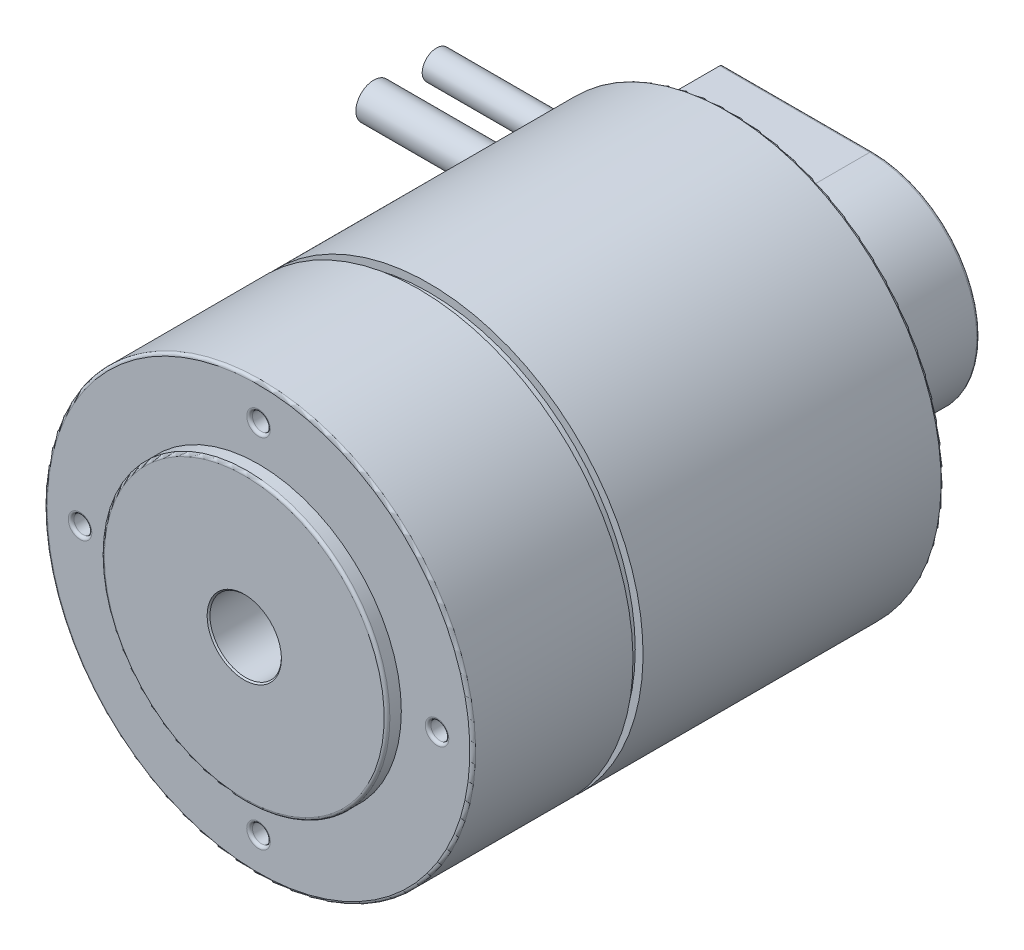
SolidWorks part; units mm, degrees
material "Copper"
ref_plane "Front Plane" through (0, 0, 0) normal (0, 0, 1) x (1, 0, 0)
ref_plane "Top Plane" through (0, 0, 0) normal (0, 1, 0) x (1, 0, 0)
ref_plane "Right Plane" through (0, 0, 0) normal (1, 0, 0) x (0, 0, -1)
sketch "Sketch1" plane through (0, 0, 0) normal (0, 0, 1) x (1, 0, 0)
  circle A0 centre (0, 0) radius 6.3437
  dimension "D1" = 12.6873
extrude "Drive Shaft Boss-Extrude1" add sketch "Sketch1" against normal blind 31.75
sketch "Sketch2" plane through (0, 0, 0) normal (0, 0, 1) x (1, 0, 0)
  line L0 (0, 0) -> (0, 8.8266) construction
  line L2 (-6.35, 10.16) -> (6.35, 10.16)
  line L3 (-6.35, 10.16) -> (-6.35, 5.08)
  line L4 (-6.35, 5.08) -> (6.35, 5.08)
  line L5 (6.35, 10.16) -> (6.35, 5.08)
  line L6 (-6.35, 10.16) -> (6.35, 5.08) construction
  line L7 (-6.35, 5.08) -> (6.35, 10.16) construction
  point P3 (0, 7.62)
  dimension "D1" = 5.08
  dimension "D2" = 12.7
  dimension "D3" = 5.08
extrude "Shaft Flat Cut-Extrude1" cut sketch "Sketch2" against normal blind 19.05
chamfer "Shaft_Chamfer1" distance 0.8128 angle 45 1 edges at (0, -6.3437, 0)
sketch "Sketch3" plane through (0, 0, -31.75) normal (0, 0, -1) x (-1, 0, 0)
  circle A0 centre (0, 0) radius 25.4
  dimension "D1" = 50.8
extrude "ServoFlangeBoss-Extrude2" add sketch "Sketch3" along normal blind 2.54
sketch "Sketch4" plane through (0, 0, -34.29) normal (0, 0, -1) x (-1, 0, 0)
  circle A0 centre (0, 0) radius 38.1
  dimension "D1" = 76.2
extrude "Motor Body Boss-Extrude3" add sketch "Sketch4" along normal blind 83.82
sketch "Sketch5" plane through (0, 0, -118.11) normal (0, 0, -1) x (-1, 0, 0)
  line L0 (0, 19.05) -> (26.67, 19.05)
  line L1 (0, -19.05) -> (26.67, -19.05)
  line L2 (26.67, 19.05) -> (26.67, -19.05)
  arc A0 (0, 19.05) -> (0, -19.05) centre (0, 0) ccw
  dimension "D1" = 38.1
  dimension "D2" = 26.67
extrude "Encoder Boss-Extrude4" add sketch "Sketch5" along normal blind 25.4
sketch "Sketch6" plane through (0, 0, 0) normal (1, 0, 0) x (0, 0, -1)
  line L0 (143.51, 0) -> (118.11, 0) construction
  line L1 (143.51, -19.05) -> (143.51, 19.05) construction
  line L2 (118.11, -19.05) -> (118.11, 19.05) construction
  circle A0 centre (125.8985, 0) radius 3.175
  circle A1 centre (137.0642, 0) radius 2.54
  dimension "D1" = 6.35
  dimension "D2" = 5.08
extrude "Cables Boss-Extrude5" add sketch "Sketch6" against normal blind 71.12
fillet "Housing Fillet1" radius 0.508 7 edges at (-13.335, -19.05, -143.51) (19.05, 0, -143.51) (-26.67, 0, -143.51) (-13.335, 19.05, -143.51) (-38.1, 0, -118.11) (-38.1, 0, -34.29) (-25.4, 0, -31.75)
sketch "Sketch7" plane through (0, 0, -34.29) normal (0, 0, 1) x (1, 0, 0)
  line L0 (0, 0) -> (50.4613, 0) construction
  line L1 (0, 0) -> (0, -50.4613) construction
  line L2 (0, 0) -> (-50.4613, 0) construction
  line L3 (0, 0) -> (0, 50.4613) construction
  circle A0 centre (0, 0) radius 31.75 construction
  circle A1 centre (31.75, 0) radius 1.5875
  circle A2 centre (0, -31.75) radius 1.5875
  circle A3 centre (-31.75, 0) radius 1.5875
  circle A4 centre (0, 31.75) radius 1.5875
  dimension "D1" = 63.5
  dimension "D2" = 3.175
  dimension "D3" = 4
extrude "Bolt Holes Cut-Extrude2" cut sketch "Sketch7" against normal blind 7.62
fillet "Bolt Hole Fillet2" radius 0.508 4 edges at (-30.1625, 0, -34.29) (1.5875, 31.75, -34.29) (33.3375, 0, -34.29) (1.5875, -31.75, -34.29)
sketch "Sketch8" plane through (0, 0, -31.75) normal (0, 0, 1) x (1, 0, 0)
  circle A0 centre (0, 0) radius 6.35
  dimension "D1" = 12.7
extrude "Shaft HoleCut-Extrude1" cut sketch "Sketch8" along normal through all and the other way blind 25.4
chamfer "Chamfer1" distance 0.254 angle 45 1 edges at (-6.35, 0, -31.75)
sketch "Sketch9" plane through (0, 0, 0) normal (1, 0, 0) x (0, 0, -1)
  line L0 (32.258, 0) -> (117.602, 0) construction
  line L1 (32.258, 25.4) -> (32.258, -25.4) construction
  line L2 (117.602, -38.1) -> (117.602, 38.1) construction
  line L4 (62.7971, 40.5325) -> (64.5879, 40.5325)
  line L5 (62.7971, 40.5325) -> (62.7971, 36.7121)
  line L6 (62.7971, 36.7121) -> (64.5879, 36.7121)
  line L7 (64.5879, 40.5325) -> (64.5879, 36.7121)
revolve "Cut-Revolve1" cut sketch "Sketch9" angle 360 about L0
